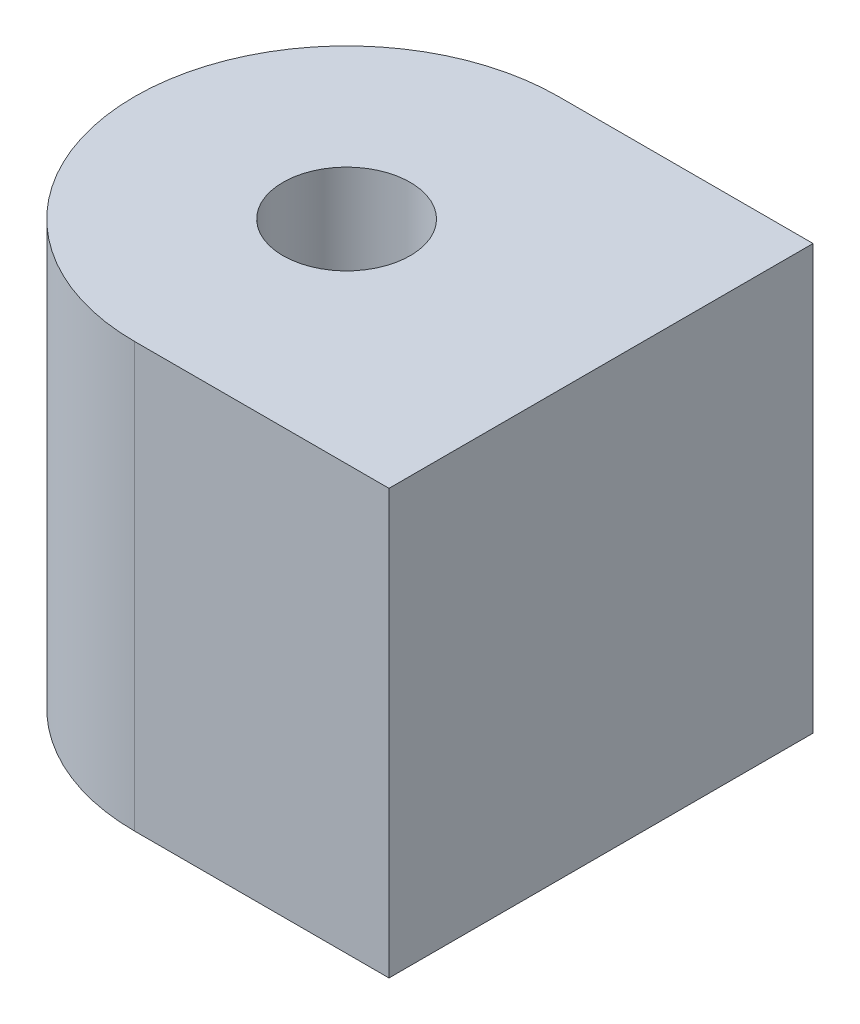
SolidWorks part; units mm, degrees
ref_plane "Front Plane" through (0, 0, 0) normal (0, 0, 1) x (1, 0, 0)
ref_plane "Top Plane" through (0, 0, 0) normal (0, 1, 0) x (1, 0, 0)
ref_plane "Right Plane" through (0, 0, 0) normal (1, 0, 0) x (0, 0, -1)
sketch "Sketch1" plane through (0, 0, 0) normal (0, 1, 0) x (1, 0, 0)
  line L0 (0, 0) -> (0, 15) construction
  line L1 (-3.75, 6.5) -> (3.75, 6.5) construction
  line L2 (3.75, 6.5) -> (2.4745, 15.3564)
  line L3 (-3.75, 6.5) -> (-2.4745, 15.3564)
  line L4 (3.7542, 6.4976) -> (12.0618, 9.8211)
  line L5 (7.5042, 0.0024) -> (14.5363, 5.5352)
  line L6 (7.5042, -0.0024) -> (14.5363, -5.5352)
  line L7 (3.7542, -6.4976) -> (12.0618, -9.8211)
  line L8 (3.75, -6.5) -> (2.4745, -15.3564)
  line L9 (-3.75, -6.5) -> (-2.4745, -15.3564)
  line L10 (-3.7542, -6.4976) -> (-12.0618, -9.8211)
  line L11 (-7.5042, -0.0024) -> (-14.5363, -5.5352)
  line L12 (-7.5042, 0.0024) -> (-14.5363, 5.5352)
  line L13 (-3.7542, 6.4976) -> (-12.0618, 9.8211)
  line L14 (-3.7542, 6.4976) -> (-3.75, 6.5)
  line L15 (3.7542, 6.4976) -> (3.75, 6.5)
  line L16 (-3.7542, -6.4976) -> (-3.75, -6.5)
  line L17 (3.75, -6.5) -> (3.7542, -6.4976)
  line L18 (-7.5042, -0.0024) -> (-7.5042, 0.0024)
  line L19 (7.5042, 0.0024) -> (7.5042, -0.0024)
  line L20 (0, -25) -> (30, -25)
  line L21 (0, 25) -> (30, 25)
  line L22 (30, 25) -> (30, -25)
  arc A0 (2.4745, 15.3564) -> (-2.4745, 15.3564) centre (0, 15) ccw
  arc A1 (14.5363, 5.5352) -> (12.0618, 9.8211) centre (12.9904, 7.5) ccw
  arc A2 (12.0618, -9.8211) -> (14.5363, -5.5352) centre (12.9904, -7.5) ccw
  arc A3 (-2.4745, -15.3564) -> (2.4745, -15.3564) centre (0, -15) ccw
  arc A4 (-14.5363, -5.5352) -> (-12.0618, -9.8211) centre (-12.9904, -7.5) ccw
  arc A5 (-12.0618, 9.8211) -> (-14.5363, 5.5352) centre (-12.9904, 7.5) ccw
  arc A6 (0, 25) -> (0, -25) centre (0, 0) ccw
  point P5 (0, 6.5)
  point P36 (0, 0)
  dimension "D4" = 5
  dimension "D6" = 50
  dimension "D7" = 30
  dimension "D1" = 7.5
  dimension "D2" = 6.5
  dimension "D3" = 15
  dimension "D5" = 6
extrude "Boss-Extrude1" add sketch "Sketch1" along normal blind 20
sketch "Sketch2" plane through (0, 20, 0) normal (0, 1, 0) x (1, 0, 0)
  line L0 (0, 25) -> (30, 25)
  line L1 (30, 25) -> (30, -25)
  line L2 (30, -25) -> (0, -25)
  arc A0 (0, 25) -> (0, -25) centre (0, 0) ccw
  circle A1 centre (0, 0) radius 7.5
  dimension "D1" = 15
extrude "Boss-Extrude2" add sketch "Sketch2" along normal blind 30
